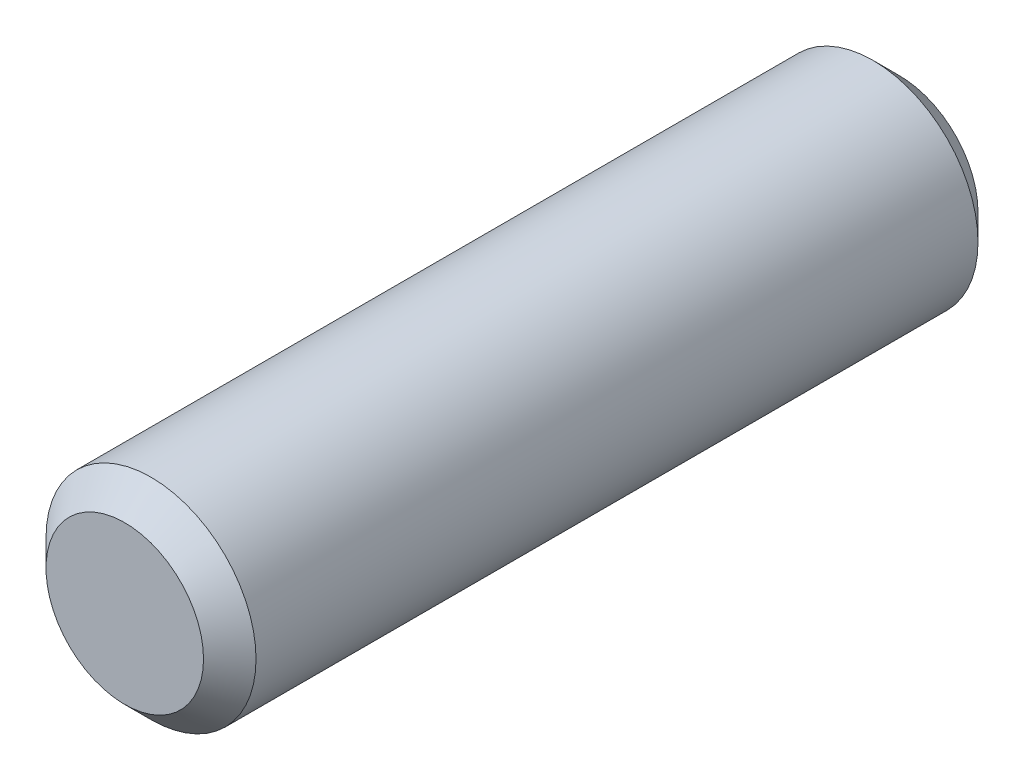
SolidWorks part; units mm, degrees
ref_plane "정면" through (0, 0, 0) normal (0, 0, 1) x (1, 0, 0)
ref_plane "윗면" through (0, 0, 0) normal (0, 1, 0) x (1, 0, 0)
ref_plane "우측면" through (0, 0, 0) normal (1, 0, 0) x (0, 0, -1)
sketch "스케치1" plane through (0, 0, 0) normal (0, 0, 1) x (1, 0, 0)
  circle A0 centre (0, 0) radius 4
  dimension "D1" = 8
extrude "보스-돌출1" add sketch "스케치1" along normal mid plane 29.5
chamfer "모따기1" distance 1 angle 45 2 edges at (4, 0, -14.75) (4, 0, 14.75)
